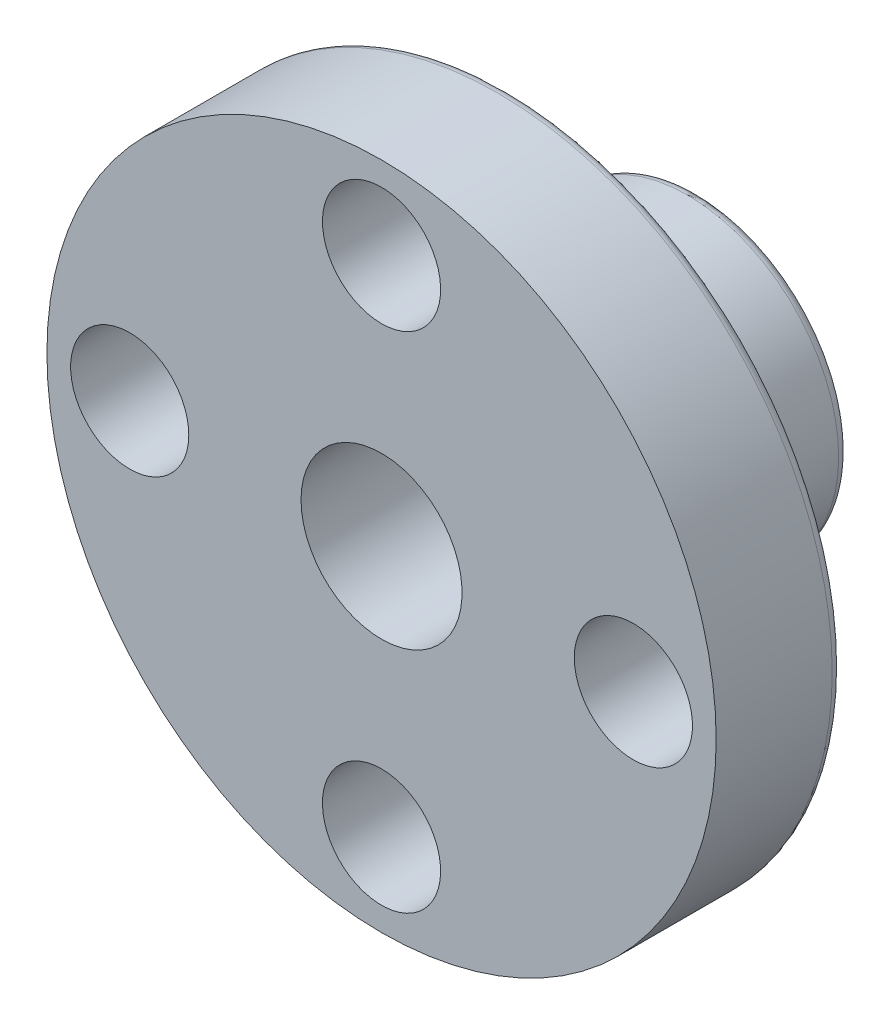
SolidWorks part; units mm, degrees
material "Alloy Steel (SS)"
ref_plane "Front Plane" through (0, 0, 0) normal (0, 0, 1) x (1, 0, 0)
ref_plane "Top Plane" through (0, 0, 0) normal (0, 1, 0) x (1, 0, 0)
ref_plane "Right Plane" through (0, 0, 0) normal (1, 0, 0) x (0, 0, -1)
sketch "Sketch1" plane through (0, 0, 0) normal (0, 0, 1) x (1, 0, 0)
  circle A0 centre (0, 0) radius 80.5625
extrude "Boss-Extrude1" add sketch "Sketch1" along normal blind 30.48
ref_plane "Plane1" through (0, 0, -2.54) normal (0, 0, -1) x (-1, 0, 0)
sketch "Sketch3" plane through (0, 0, 0) normal (0, 0, -1) x (-1, 0, 0)
  circle A0 centre (0, 0) radius 36.4068
extrude "Boss-Extrude2" add sketch "Sketch3" along normal blind 45.72
sketch "Sketch4" plane through (0, 0, -45.72) normal (0, 0, -1) x (-1, 0, 0)
  circle A0 centre (0, 0) radius 19.3839
extrude "Cut-Extrude1" cut sketch "Sketch4" against normal through all
sketch "Sketch5" plane through (0, 0, -2.54) normal (0, 0, -1) x (-1, 0, 0)
  line L0 (0, 0) -> (-94.8788, 0) construction
  line L1 (-94.8788, 0) -> (90.0133, 0) construction
  line L2 (0, 0) -> (0, -102.9258) construction
  line L3 (0, -102.9258) -> (0, 102.1772) construction
  circle A0 centre (0, 0) radius 60.6326 construction
  circle A1 centre (-60.6326, 0) radius 14.2225
extrude "Cut-Extrude2" cut sketch "Sketch5" against normal through all
pattern_circular "CirPattern2" count 4 over 360 about axis through (0, 0, 0) along (0, 0, 1) of "Cut-Extrude2"
fillet "Fillet1" radius 2.54 2 edges at (36.4068, 0, 0) (-36.4068, 0, -45.72)
fillet "Fillet2" radius 2.54 1 edges at (80.5625, 0, 0)
chamfer "Chamfer1" [suppressed] distance 2.54 angle 45
